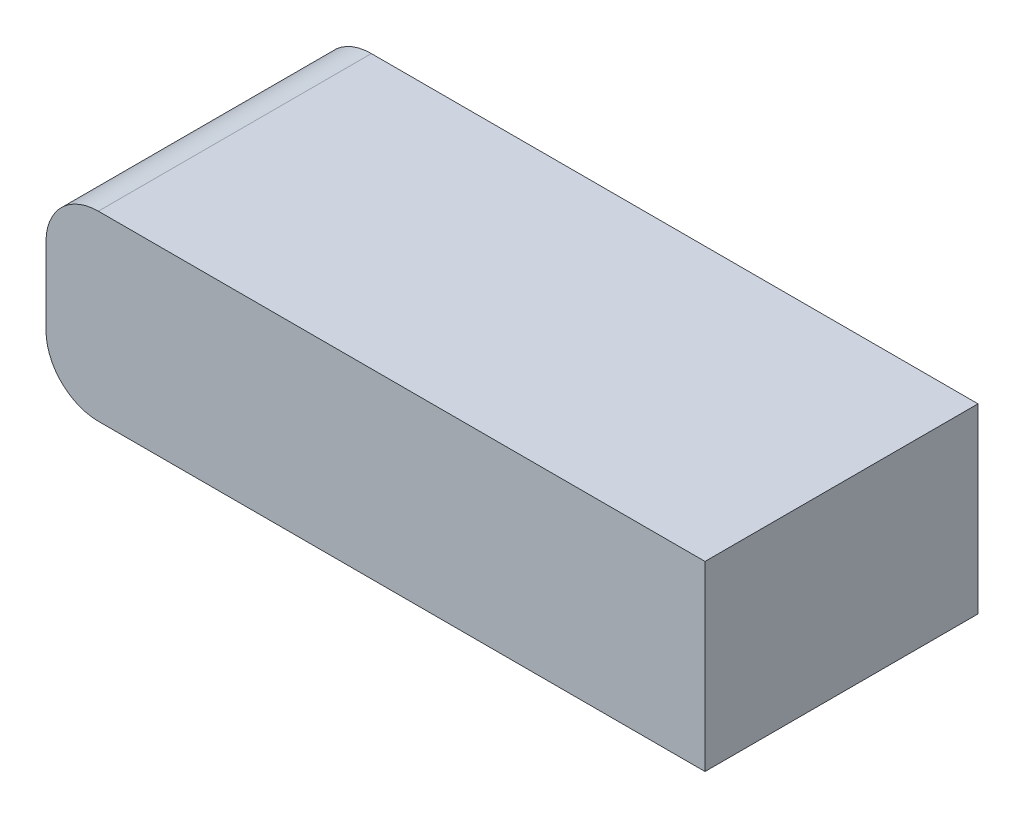
SolidWorks part; units mm, degrees
ref_plane "Ebene vorne" through (0, 0, 0) normal (0, 0, 1) x (1, 0, 0)
ref_plane "Ebene oben" through (0, 0, 0) normal (0, 1, 0) x (1, 0, 0)
ref_plane "Ebene rechts" through (0, 0, 0) normal (1, 0, 0) x (0, 0, -1)
sketch "Skizze1" plane through (0, 0, 0) normal (0, 0, 1) x (1, 0, 0)
  line L0 (0, 0) -> (355.5555, 0)
  line L1 (355.5555, 0) -> (355.5555, 106.666)
  line L2 (355.5555, 106.666) -> (0, 106.666)
  line L3 (-30.7028, 75.9632) -> (-30.7028, 30.7028)
  arc A0 (0, 106.666) -> (-30.7028, 75.9632) centre (0, 75.9632) ccw
  arc A1 (-30.7028, 30.7028) -> (0, 0) centre (0, 30.7028) ccw
  dimension "D1" = 355.5555
  dimension "D2" = 106.666
extrude "Aufsatz-Linear austragen1" add sketch "Skizze1" along normal blind 160
